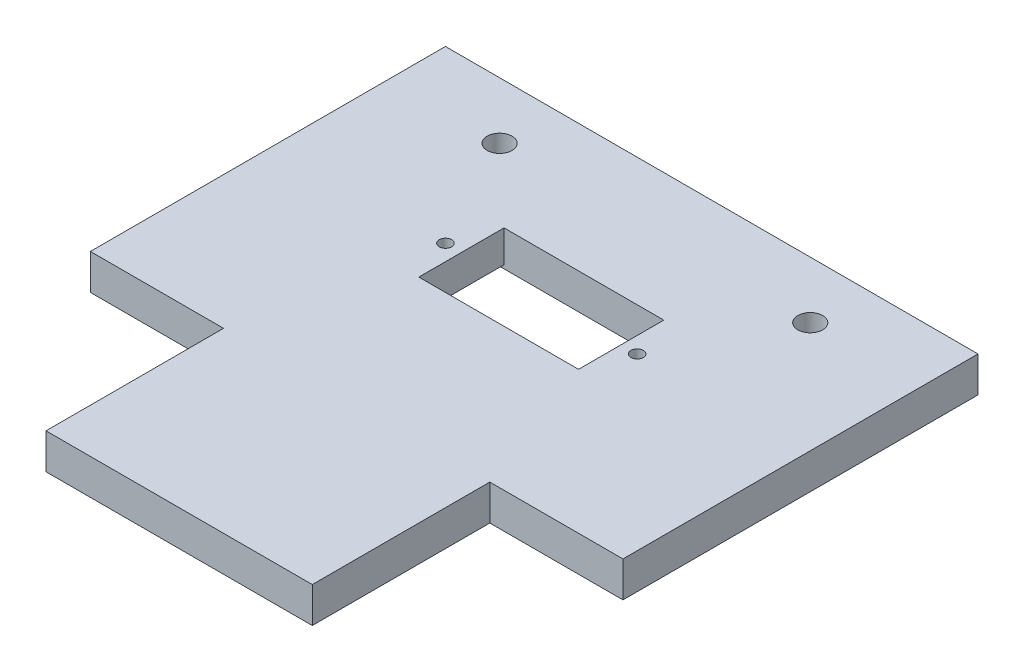
SolidWorks part; units mm, degrees
ref_plane "Front Plane" through (0, 0, 0) normal (0, 0, 1) x (1, 0, 0)
ref_plane "Top Plane" through (0, 0, 0) normal (0, 1, 0) x (1, 0, 0)
ref_plane "Right Plane" through (0, 0, 0) normal (1, 0, 0) x (0, 0, -1)
sketch "Sketch1" plane through (0, 0, 0) normal (0, 1, 0) x (1, 0, 0)
  line L0 (0, 0) -> (0, -43.9642) construction
  line L2 (-38.1, -12.7) -> (-38.1, 38.1)
  line L3 (-38.1, 38.1) -> (38.1, 38.1)
  line L4 (38.1, 38.1) -> (38.1, -12.7)
  line L7 (0, -43.9642) -> (0, 48.5365) construction
  line L8 (-19.05, -38.1) -> (19.05, -38.1)
  line L11 (-38.1, -12.7) -> (-19.05, -12.7)
  line L12 (-19.05, -38.1) -> (-19.05, -12.7)
  line L15 (38.1, -12.7) -> (19.05, -12.7)
  line L16 (19.05, -38.1) -> (19.05, -12.7)
  point P0 (0, 0)
  dimension "D1" = 76.2
  dimension "D2" = 50.8
  dimension "D3" = 38.1
  dimension "D4" = 76.2
extrude "Boss-Extrude1" add sketch "Sketch1" along normal blind 5.08
sketch "Sketch2" plane through (0, 5.08, 0) normal (0, 1, 0) x (1, 0, 0)
  line L0 (0, 44.8871) -> (0, -50.8249) construction
  line L2 (-19.05, -38.1) -> (19.05, -38.1) construction
  circle A0 centre (-22.225, 29.972) radius 1.778
  circle A1 centre (22.225, 29.972) radius 1.778
  dimension "D3" = 3.556
  dimension "D1" = 68.072
  dimension "D2" = 22.225
extrude "Cut-Extrude1" cut sketch "Sketch2" against normal through all
sketch "Sketch3" plane through (0, 5.08, 0) normal (0, 1, 0) x (1, 0, 0)
  line L0 (-38.1, 19.812) -> (38.1, 19.812) construction
  line L1 (-38.1, 38.1) -> (-38.1, -12.7) construction
  line L2 (38.1, -12.7) -> (38.1, 38.1) construction
  line L3 (38.1, 38.1) -> (-38.1, 38.1) construction
  line L4 (0, -43.0032) -> (0, 82.6272) construction
  line L6 (-11.43, 7.62) -> (11.43, 7.62)
  line L7 (-11.43, 7.62) -> (-11.43, 19.812)
  line L8 (-11.43, 19.812) -> (11.43, 19.812)
  line L9 (11.43, 7.62) -> (11.43, 19.812)
  line L10 (-11.43, 7.62) -> (11.43, 19.812) construction
  line L11 (-11.43, 19.812) -> (11.43, 7.62) construction
  point P8 (0, 13.716)
  point P12 (0, 19.812)
  dimension "D1" = 18.288
  dimension "D2" = 12.192
  dimension "D3" = 22.86
extrude "Cut-Extrude2" cut sketch "Sketch3" against normal blind 4.572
sketch "Sketch4" plane through (0, 0, 0) normal (0, -1, 0) x (1, 0, 0)
  line L0 (0, -38.1) -> (0, 38.1) construction
  line L1 (38.1, -38.1) -> (-38.1, -38.1) construction
  line L2 (-19.05, 38.1) -> (19.05, 38.1) construction
  line L3 (38.1, -19.812) -> (-38.1, -19.812) construction
  line L4 (38.1, 12.7) -> (38.1, -38.1) construction
  line L5 (-38.1, -38.1) -> (-38.1, 12.7) construction
  line L7 (16.51, -7.62) -> (-16.51, -7.62)
  line L8 (16.51, -7.62) -> (16.51, -19.812)
  line L9 (16.51, -19.812) -> (-16.51, -19.812)
  line L10 (-16.51, -7.62) -> (-16.51, -19.812)
  line L11 (16.51, -7.62) -> (-16.51, -19.812) construction
  line L12 (16.51, -19.812) -> (-16.51, -7.62) construction
  point P12 (0, -13.716)
  dimension "D1" = 18.288
  dimension "D2" = 33.02
  dimension "D3" = 12.192
extrude "Cut-Extrude3" cut sketch "Sketch4" against normal up to surface (0.508 mm away) up to face at (0, 0.508, -13.716)
sketch "Sketch5" plane through (0, 0.508, 0) normal (0, -1, 0) x (1, 0, 0)
  line L0 (0, -37.8963) -> (0, 1.0925) construction
  circle A0 centre (-13.716, -13.716) radius 0.889
  circle A1 centre (13.716, -13.716) radius 0.889
  dimension "D3" = 1.778
  dimension "D1" = 27.432
  dimension "D2" = 13.716
extrude "Cut-Extrude4" cut sketch "Sketch5" against normal through all
